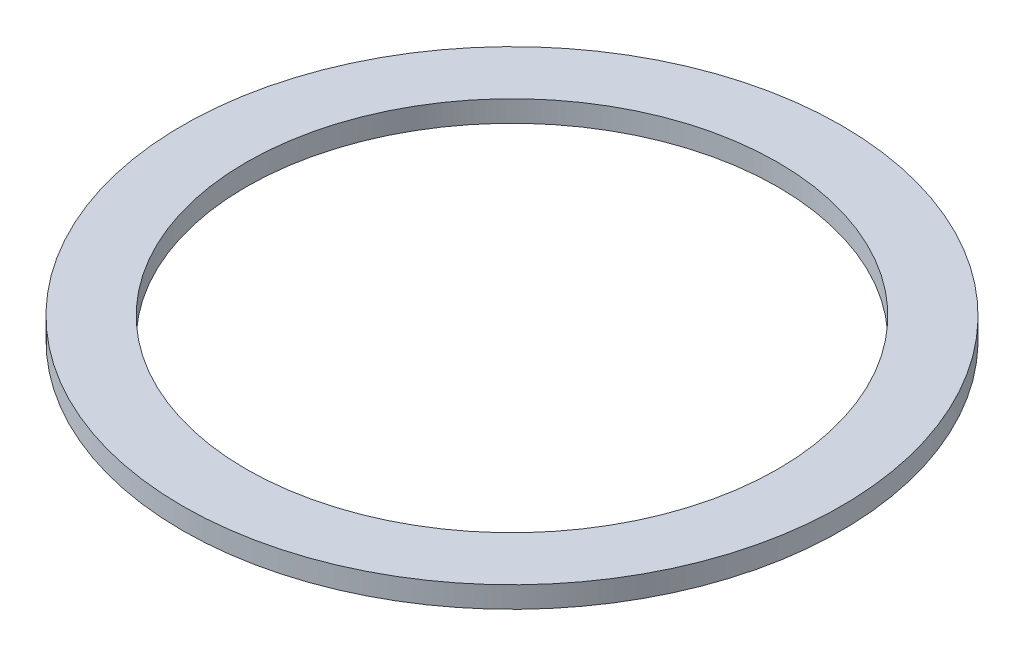
SolidWorks part; units mm, degrees
material "Stainless Steel (ferritic)"
ref_plane "Front Plane" through (0, 0, 0) normal (0, 0, 1) x (1, 0, 0)
ref_plane "Top Plane" through (0, 0, 0) normal (0, 1, 0) x (1, 0, 0)
ref_plane "Right Plane" through (0, 0, 0) normal (1, 0, 0) x (0, 0, -1)
sketch "Sketch1" plane through (0, 0, 0) normal (0, 1, 0) x (1, 0, 0)
  circle A0 centre (0, 0) radius 31
  circle A1 centre (0, 0) radius 25
  dimension "D1" = 50
  dimension "OD" = 62
extrude "Boss-Extrude1" add sketch "Sketch1" along normal blind 2
